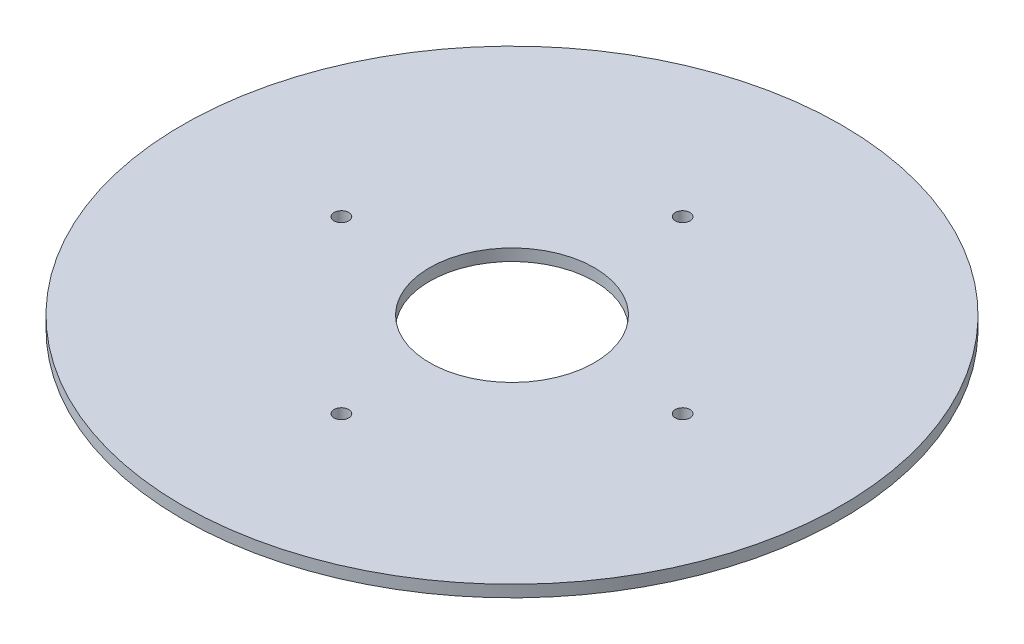
SolidWorks part; units mm, degrees
ref_plane "Front Plane" through (0, 0, 0) normal (0, 0, 1) x (1, 0, 0)
ref_plane "Top Plane" through (0, 0, 0) normal (0, 1, 0) x (1, 0, 0)
ref_plane "Right Plane" through (0, 0, 0) normal (1, 0, 0) x (0, 0, -1)
sketch "Sketch1" plane through (0, 0, 0) normal (0, 1, 0) x (1, 0, 0)
  line L0 (-46.0328, 0) -> (0, 46.0328) construction
  line L11 (0, 46.0328) -> (46.0328, 0) construction
  line L12 (46.0328, 0) -> (0, -46.0328) construction
  line L13 (0, -46.0328) -> (-46.0328, 0) construction
  line L14 (0, -46.0328) -> (0, 46.0328) construction
  line L15 (46.0328, 0) -> (-46.0328, 0) construction
  circle A0 centre (0, 0) radius 88.9
  circle A5 centre (0, 46.0328) radius 1.9844
  circle A6 centre (46.0328, 0) radius 1.9844
  circle A7 centre (0, -46.0328) radius 1.9844
  circle A8 centre (-46.0328, 0) radius 1.9844
  dimension "D1" = 177.8
extrude "Boss-Extrude1" add sketch "Sketch1" along normal blind 3.175
sketch "Sketch2" plane through (0, 0, 0) normal (0, -1, 0) x (1, 0, 0)
  circle A0 centre (0, 0) radius 22.225
  dimension "D1" = 44.45
extrude "Cut-Extrude1" cut sketch "Sketch2" against normal through all
